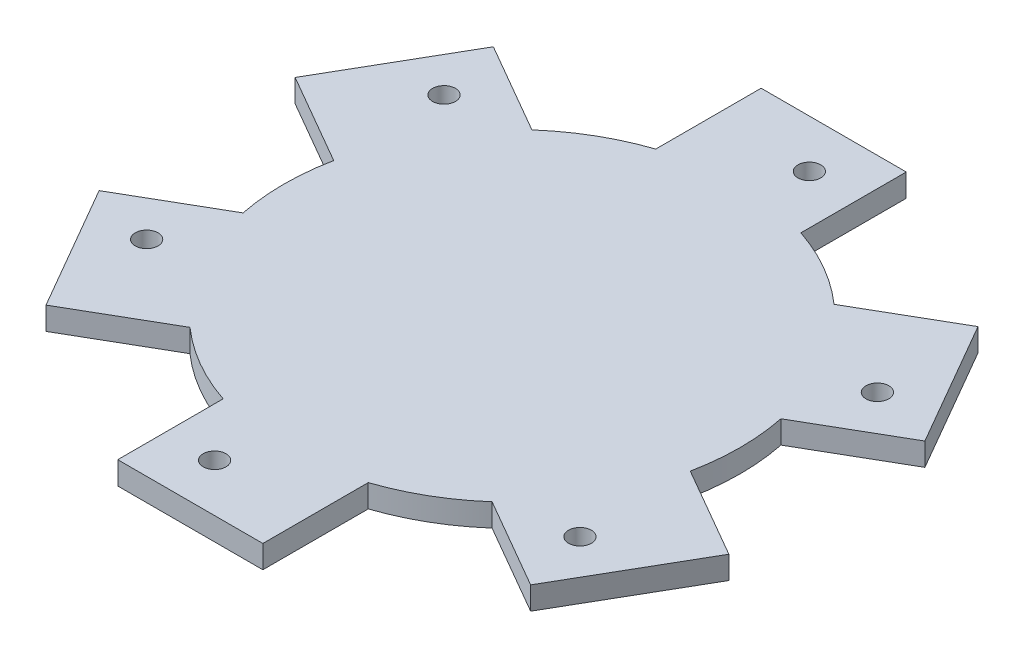
SolidWorks part; units mm, degrees
ref_plane "Front Plane" through (0, 0, 0) normal (0, 0, 1) x (1, 0, 0)
ref_plane "Top Plane" through (0, 0, 0) normal (0, 1, 0) x (1, 0, 0)
ref_plane "Right Plane" through (0, 0, 0) normal (1, 0, 0) x (0, 0, -1)
sketch "Sketch1" plane through (0, 0, 0) normal (0, 1, 0) x (1, 0, 0)
  line L1 (15.9, -70.5) -> (-15.9, -70.5)
  line L2 (15.9, -70.5) -> (15.9, 70.5)
  line L3 (15.9, 70.5) -> (-15.9, 70.5)
  line L4 (-15.9, -70.5) -> (-15.9, 70.5)
  line L5 (15.9, -70.5) -> (-15.9, 70.5) construction
  line L6 (15.9, 70.5) -> (-15.9, -70.5) construction
  circle A0 centre (0, 0) radius 50
  dimension "D1" = 100
  dimension "D2" = 31.8
  dimension "D3" = 70.5
extrude "Boss-Extrude1" add sketch "Sketch1" along normal blind 5 contours L4 A0 | L2 A0 L4 | A0 L4 L1 L2 | A0 L2 L3 L4 | L2 A0
pattern_circular "CirPattern1" count 3 every 60 about axis through (0, 0, 0) along (0, 1, 0) of "Boss-Extrude1"
sketch "Sketch2" plane through (0, 5, 0) normal (0, 1, 0) x (1, 0, 0)
  line L0 (69.0048, -21.4802) -> (53.1048, -49.0198) construction
  line L1 (53.1048, -49.0198) -> (33.1035, -37.4721) construction
  circle A0 centre (49.3765, -34.4774) radius 2.5
  dimension "D1" = 5
  dimension "D2" = 10.5
  dimension "D3" = 10.73
extrude "Cut-Extrude1" cut sketch "Sketch2" against normal through all
pattern_circular "CirPattern2" count 6 every 60 about axis through (0, 0, 0) along (0, 1, 0) of "Cut-Extrude1"
